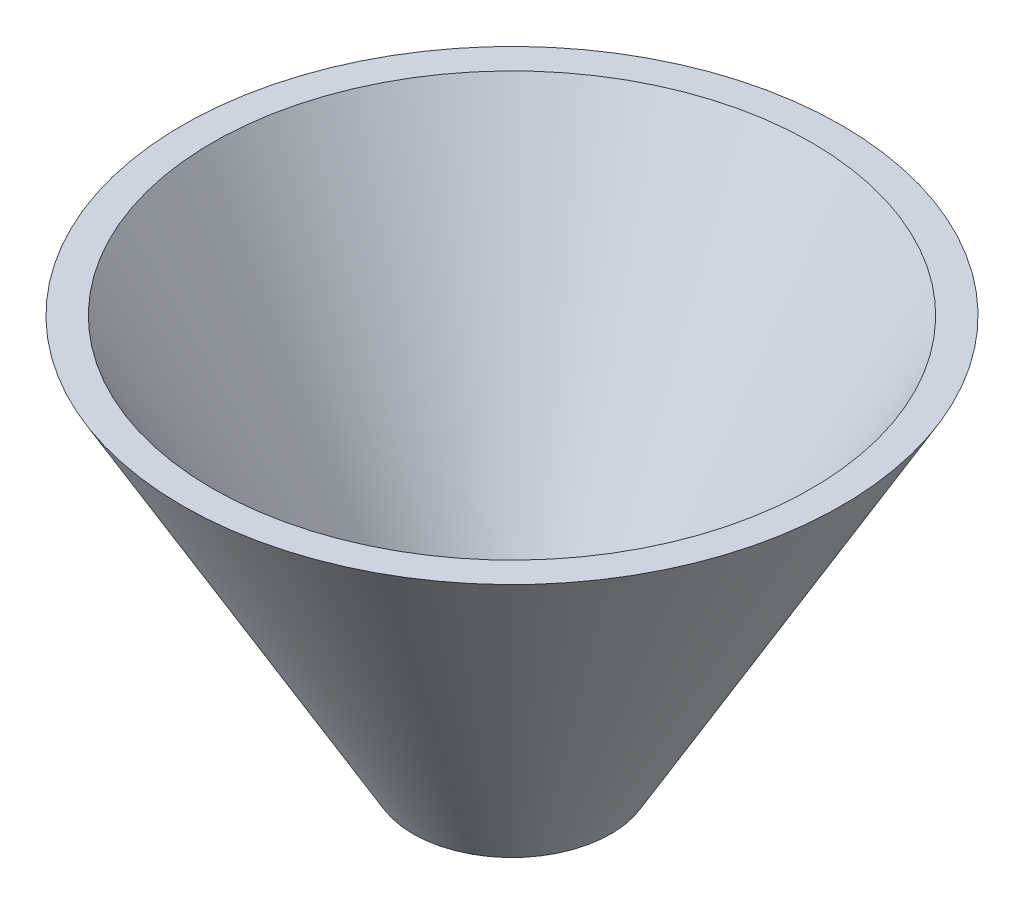
SolidWorks part; units mm, degrees
ref_plane "前视基准面" through (0, 0, 0) normal (0, 0, 1) x (1, 0, 0)
ref_plane "上视基准面" through (0, 0, 0) normal (0, 1, 0) x (1, 0, 0)
ref_plane "右视基准面" through (0, 0, 0) normal (1, 0, 0) x (0, 0, -1)
other "Configuration Table"
sketch "草图1" plane through (0, 0, 0) normal (0, 0, 1) x (1, 0, 0)
  line L0 (0, 0) -> (4.95, 0)
  line L1 (4.95, 0) -> (16.497, 20)
  line L2 (0, 0) -> (0, 20)
  line L3 (16.497, 20) -> (0, 20)
  dimension "D1" = 4.95
  dimension "D2" = 120
  dimension "D3" = 20
revolve "旋转1" add sketch "草图1" angle 360 about L2
sketch "草图2" plane through (0, 0, 0) normal (0, 0, 1) x (1, 0, 0)
  line L0 (0, 0) -> (3.45, 0)
  line L1 (3.45, 0) -> (14.997, 20)
  line L2 (0, 0) -> (0, 20)
  line L3 (14.997, 20) -> (0, 20)
  dimension "D1" = 3.45
  dimension "D2" = 120
  dimension "D3" = 20
revolve "切除-旋转1" cut sketch "草图2" angle 360 about L2
